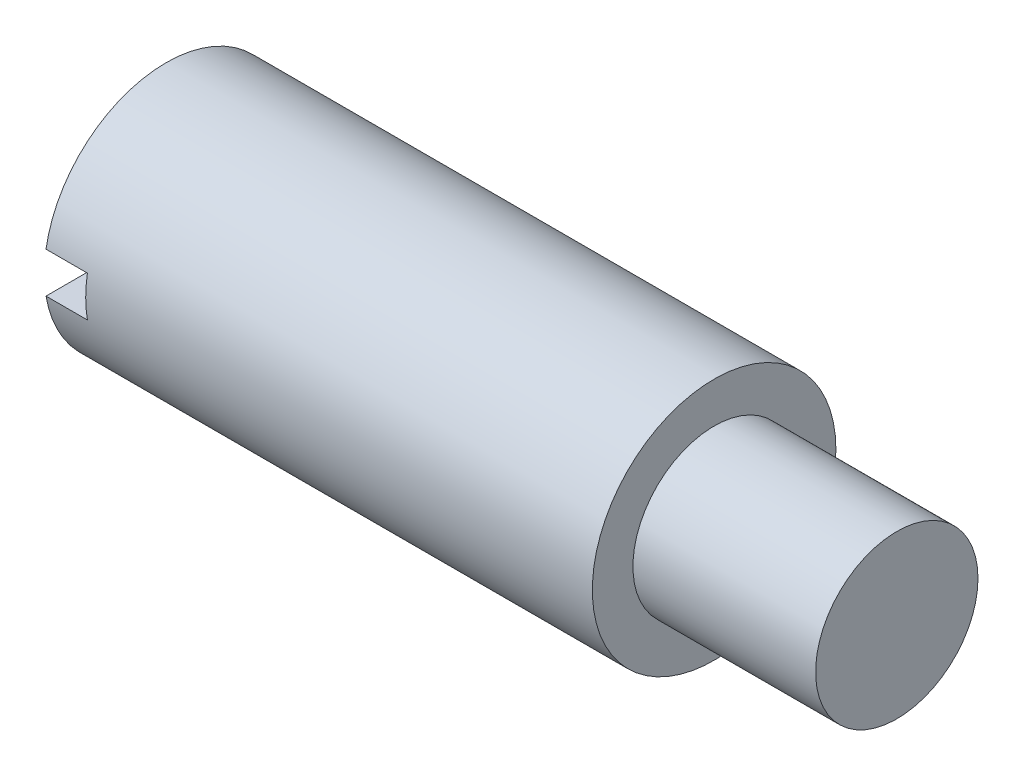
SolidWorks part; units mm, degrees
ref_plane "Front Plane" through (0, 0, 0) normal (0, 0, 1) x (1, 0, 0)
ref_plane "Top Plane" through (0, 0, 0) normal (0, 1, 0) x (1, 0, 0)
ref_plane "Right Plane" through (0, 0, 0) normal (1, 0, 0) x (0, 0, -1)
sketch "Sketch1" plane through (0, 0, 0) normal (0, 0, 1) x (1, 0, 0)
  line L0 (9, 0) -> (-9, 0)
  line L1 (-9, 0) -> (-9, 3)
  line L2 (-9, 3) -> (4.5, 3)
  line L3 (4.5, 3) -> (4.5, 2)
  line L4 (4.5, 2) -> (9, 2)
  line L5 (9, 2) -> (9, 0)
  point P4 (0, 0)
  dimension "D1" = 18
revolve "Revolve1" add sketch "Sketch1" angle 360 about L0
sketch "Sketch2" plane through (0, 0, 0) normal (0, 0, 1) x (1, 0, 0)
  line L0 (-9, 3) -> (-9, -3) construction
  line L1 (-10.02, -0.5) -> (-7.98, -0.5)
  line L2 (-10.02, -0.5) -> (-10.02, 0.5)
  line L3 (-10.02, 0.5) -> (-7.98, 0.5)
  line L4 (-7.98, -0.5) -> (-7.98, 0.5)
  line L5 (-10.02, -0.5) -> (-7.98, 0.5) construction
  line L6 (-10.02, 0.5) -> (-7.98, -0.5) construction
  point P0 (-9, 0)
  dimension "D1" = 7.98
  dimension "D2" = 0.5
extrude "Cut-Extrude1" cut sketch "Sketch2" against normal through all both and the other way through all
